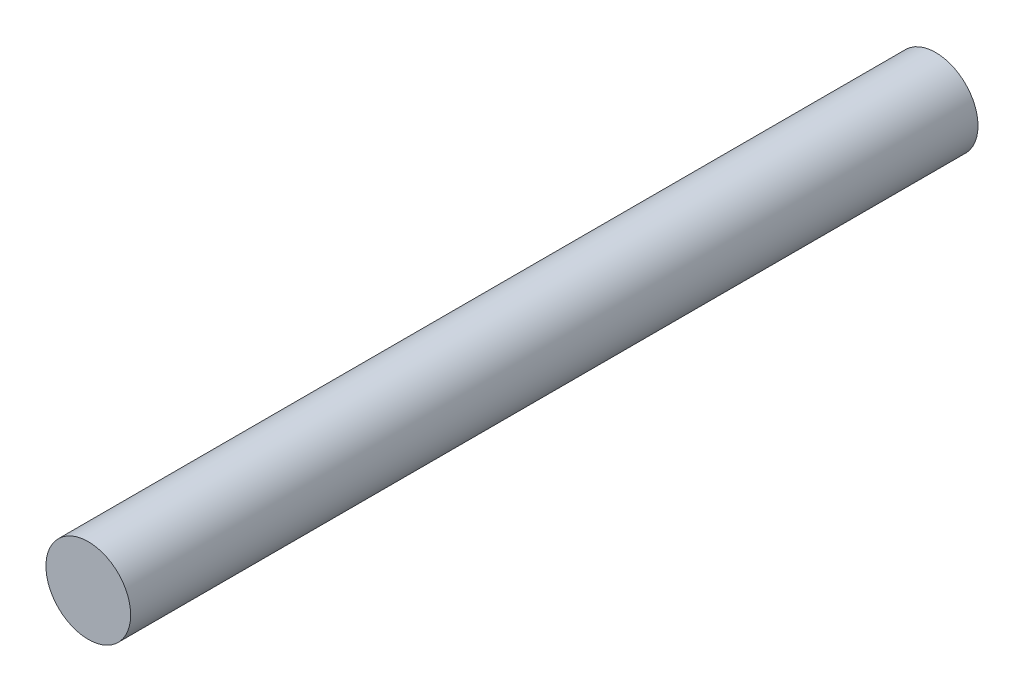
SolidWorks part; units mm, degrees
ref_plane "Płaszczyzna przednia" through (0, 0, 0) normal (0, 0, 1) x (1, 0, 0)
ref_plane "Płaszczyzna górna" through (0, 0, 0) normal (0, 1, 0) x (1, 0, 0)
ref_plane "Płaszczyzna prawa" through (0, 0, 0) normal (1, 0, 0) x (0, 0, -1)
sketch "Szkic1" plane through (0, 0, 0) normal (0, 0, 1) x (1, 0, 0)
  circle A0 centre (0, 0) radius 2.5
  dimension "D1" = 5
extrude "Dodanie-wyciągnięcie1" add sketch "Szkic1" along normal blind 50
